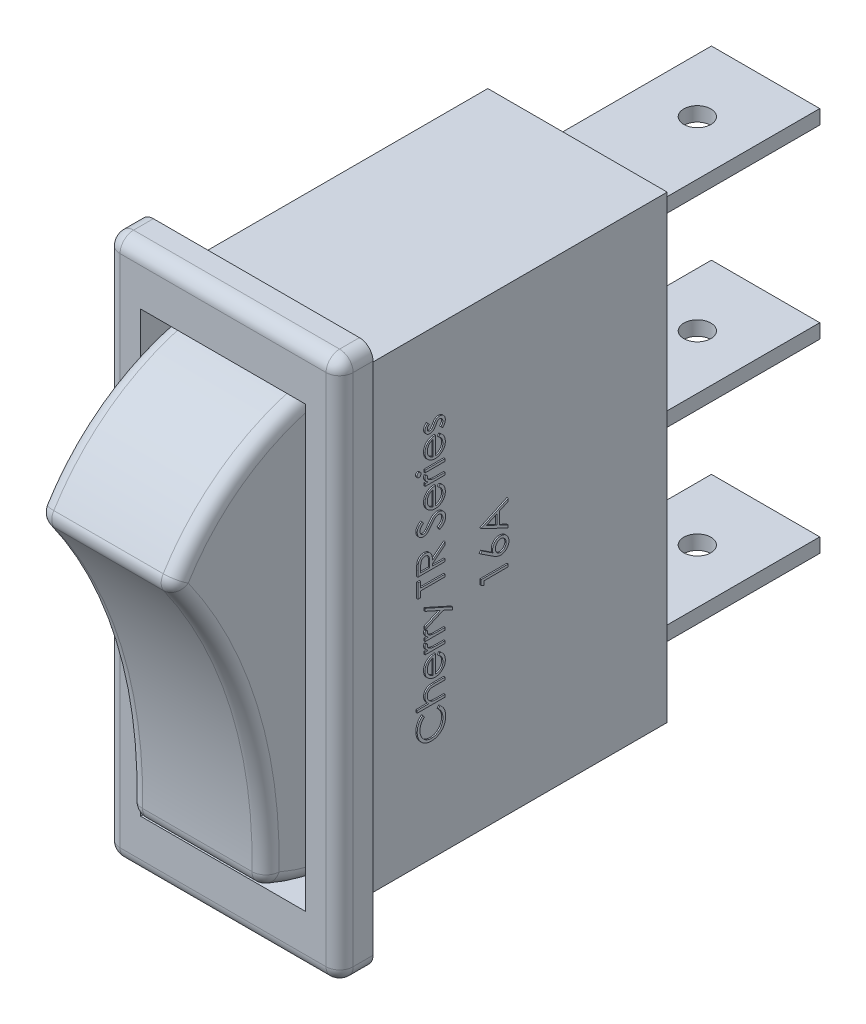
SolidWorks part; units mm, degrees
material "ABS"
ref_plane "Front Plane" through (0, 0, 0) normal (0, 0, 1) x (1, 0, 0)
ref_plane "Top Plane" through (0, 0, 0) normal (0, 1, 0) x (1, 0, 0)
ref_plane "Right Plane" through (0, 0, 0) normal (1, 0, 0) x (0, 0, -1)
sketch "Sketch1" plane through (0, 0, 0) normal (0, 0, 1) x (1, 0, 0)
  line L0 (0, -55) -> (0, 55) construction
  line L1 (-5.2578, 13.462) -> (5.2578, 13.462)
  line L2 (-5.2578, 13.462) -> (-5.2578, -13.462)
  line L3 (-5.2578, -13.462) -> (5.2578, -13.462)
  line L4 (5.2578, 13.462) -> (5.2578, -13.462)
  line L5 (55, 0) -> (-55, 0) construction
  point P4 (0, 13.462)
  point P7 (-5.2578, 0)
  dimension "D1" = 10.5156
  dimension "D2" = 26.924
extrude "main body" add sketch "Sketch1" against normal blind 18.8214
sketch "Sketch2" plane through (0, 0, 0) normal (0, 0, 1) x (1, 0, 0)
  line L4 (-5.2578, 13.462) -> (-5.2578, -13.462)
  line L5 (-5.2578, -13.462) -> (5.2578, -13.462)
  line L6 (5.2578, -13.462) -> (5.2578, 13.462)
  line L7 (5.2578, 13.462) -> (-5.2578, 13.462)
  line L8 (-5.2578, 13.462) -> (-5.2578, -13.462) construction
  line L9 (-5.2578, -13.462) -> (5.2578, -13.462) construction
  line L10 (5.2578, -13.462) -> (5.2578, 13.462) construction
  line L11 (5.2578, 13.462) -> (-5.2578, 13.462) construction
  line L16 (-4.464, 12.6683) -> (-4.464, -12.6682)
  line L17 (-4.464, -12.6682) -> (4.4641, -12.6682)
  line L18 (4.4641, -12.6682) -> (4.4641, 12.6682)
  line L19 (4.4641, 12.6682) -> (-4.464, 12.6683)
  line L20 (-4.464, 12.6683) -> (-4.464, -12.6682)
  line L21 (-4.464, -12.6682) -> (4.4641, -12.6682)
  line L22 (4.4641, -12.6682) -> (4.4641, 12.6682)
  line L23 (4.4641, 12.6682) -> (-4.464, 12.6683)
  dimension "D1" = 0
  dimension "D2" = 0.7937
extrude "main body light" cut sketch "Sketch2" against normal blind 17.4625
sketch "Sketch3" plane through (0, 0, 0) normal (0, 0, 1) x (1, 0, 0)
  line L0 (0, -10.3518) -> (0, 10.3518) construction
  line L1 (-6.8326, 15.875) -> (6.8326, 15.875)
  line L2 (-6.8326, 15.875) -> (-6.8326, -15.875)
  line L3 (-6.8326, -15.875) -> (6.8326, -15.875)
  line L4 (6.8326, 15.875) -> (6.8326, -15.875)
  line L5 (5.7836, 0) -> (-5.7836, 0) construction
  line L6 (-4.8326, 12.875) -> (4.8326, 12.875)
  line L7 (4.8326, 12.875) -> (4.8326, -12.875)
  line L8 (-4.8326, -12.875) -> (4.8326, -12.875)
  line L9 (-4.8326, 12.875) -> (-4.8326, -12.875)
  point P4 (0, 15.875)
  point P7 (-6.8326, 0)
  point P14 (-4.8326, 0)
  point P15 (0, 12.875)
  dimension "D1" = 13.6652
  dimension "D2" = 31.75
  dimension "D3" = 3
  dimension "D4" = 2
extrude "flange" add sketch "Sketch3" along normal blind 1.9558
sketch "Sketch4" plane through (0, 0, 0) normal (1, 0, 0) x (0, 0, -1)
  line L0 (8.8221, -10.3824) -> (3.9016, 0)
  line L1 (1.0592, 12.624) -> (3.9016, 0)
  line L2 (-1.9558, -15.875) -> (0, -15.875) construction
  line L3 (7.5159, 0) -> (-7.5159, 0) construction
  line L4 (-8.9408, 6.35) -> (-8.9408, -1.9309) construction
  line L5 (2.159, 0) -> (4.3189, 0) construction
  line L7 (-1.9558, -15.875) -> (-1.9558, 15.875) construction
  line L8 (-1.9558, 15.875) -> (0, 15.875) construction
  line L10 (1.0592, 15.4459) -> (1.0592, -1.9309) construction
  line L11 (1.0592, 6.35) -> (1.0592, -1.9309) construction
  line L12 (17.4625, 12.6682) -> (0, 12.6682) construction
  line L13 (-4.7056, -2.0778) -> (2.1432, 0.1504) construction
  arc A0 (-8.9408, 6.35) -> (-3.4798, -11.43) centre (-31.7201, -10.3752) cw
  arc A1 (-8.9408, 6.35) -> (0, 12.6682) centre (2.1432, 0.1504) cw
  circle A3 centre (2.159, 0) radius 1.5875
  arc A4 (0, 12.6682) -> (1.0592, 12.624) centre (0, -0.0318) cw
  arc A5 (6.9178, -11.8048) -> (8.8221, -10.3824) centre (0.3031, -0.9634) ccw
  arc A6 (-3.4798, -11.43) -> (6.9178, -11.8048) centre (2.1432, 0.1504) ccw
  point P12 (-0.9779, 15.875)
  dimension "D1" = 28.26
  dimension "D6" = 12.7
  dimension "D7" = 4.1148
  dimension "D8" = 3.175
  dimension "D2" = 6.985
  dimension "D3" = 9.525
  dimension "D4" = 1.524
  dimension "D5" = 4.445
  dimension "D9" = 10
  dimension "D10" = 167.332
  dimension "D11" = 12.9401
extrude "switch body and profile" add sketch "Sketch4" along normal mid plane 8 separate body
fillet "Fillet1" radius 0.7937 8 edges at (-6.8326, -15.875, 0.9779) (6.8326, -15.875, 0.9779) (-6.8326, 15.875, 0.9779) (6.8326, 15.875, 0.9779) (-6.8326, 0, 1.9558) (0, -15.875, 1.9558) (6.8326, 0, 1.9558) (0, 15.875, 1.9558)
fillet "Fillet2" radius 0.7937 8 edges at (0, 6.35, 8.9408) (-4, -12.7146, -1.6795) (4, -12.7146, -1.6795) (0, -11.43, 3.4798) (-4, -2.0778, 4.7056) (4, -2.0778, 4.7056) (4, 10.522, 5.1862) (-4, 10.522, 5.1862)
sketch "Sketch5" plane through (0, 0, -18.8214) normal (0, 0, -1) x (-1, 0, 0)
  line L0 (5.2578, -13.462) -> (-5.2578, -13.462) construction
  line L1 (-3.175, -10.5918) -> (3.175, -10.5918)
  line L2 (-3.175, -10.5918) -> (-3.175, -11.43)
  line L3 (-3.175, -11.43) -> (3.175, -11.43)
  line L4 (3.175, -10.5918) -> (3.175, -11.43)
  line L5 (0, 15.1853) -> (0, -15.1853) construction
  line L6 (-3.175, -0.5588) -> (3.175, -0.5588)
  line L7 (-3.175, 0.2794) -> (-3.175, -0.5588)
  line L8 (-3.175, 0.2794) -> (3.175, 0.2794)
  line L9 (3.175, 0.2794) -> (3.175, -0.5588)
  line L10 (-3.175, 10.3124) -> (3.175, 10.3124)
  line L11 (-3.175, 11.1506) -> (-3.175, 10.3124)
  line L12 (-3.175, 11.1506) -> (3.175, 11.1506)
  line L13 (3.175, 11.1506) -> (3.175, 10.3124)
  point P6 (0, -10.5918)
  dimension "D1" = 6.35
  dimension "D2" = 0.8382
  dimension "D3" = 2.032
  dimension "D4" = 10.033
extrude "Extrude5" add sketch "Sketch5" along normal blind 11.0236
hole_wizard "1/16 (0.0625) Diameter Hole1" positions "Sketch7" profile "Sketch6" hole size "1/16" standard "Ansi Inch" end condition through all
sketch "Sketch7" plane through (0, 11.1506, 0) normal (0, 1, 0) x (-1, 0, 0)
  line L0 (3.175, -29.845) -> (-3.175, -29.845) construction
  line L1 (0, 17.4625) -> (0, -17.4625) construction
  point P0 (0, -25.845)
  dimension "D1" = 4
sketch "Sketch6" plane through (0, 11.1506, -25.845) normal (1, 0, 0) x (0, 0, 1)
  line L0 (0, 0) -> (0, 27.0256)
  line L1 (0, 27.0256) -> (0.7937, 27.0256)
  line L2 (0.7937, 27.0256) -> (0.7937, 0)
  line L5 (0.7937, 0) -> (0, 0)
  line L11 (0, -6.35) -> (0, 107.95) construction
  dimension "Thru Hole Dia." = 1.5875
  dimension "Thru Hole Depth" = 27.0256
sketch "Sketch8" plane through (5.2578, 0, 0) normal (1, 0, 0) x (0, 0, -1)
  line L0 (5.7184, -8.3553) -> (5.7184, 9.6822) construction
  text T0 "Cherry TR Series\r\n16A" font "Century Gothic" height 1.5875
extrude "label text" add sketch "Sketch8" along normal blind 0.0762
sketch "cut pattern" plane through (0, 0, 0) normal (0, 0, -1) x (-1, 0, 0)
  line L0 (5.4991, 15.367) -> (-5.4991, 15.367)
  line L1 (-5.4991, 15.367) -> (-5.4991, -15.367)
  line L2 (-5.4991, -15.367) -> (5.4991, -15.367)
  line L3 (5.4991, -15.367) -> (5.4991, 15.367)
  line L4 (5.2578, -13.462) -> (5.2578, 13.462)
  line L5 (-5.2578, -13.462) -> (5.2578, -13.462)
  line L6 (-5.2578, 13.462) -> (-5.2578, -13.462)
  line L7 (5.2578, 13.462) -> (-5.2578, 13.462)
  line L8 (5.2578, -13.462) -> (5.2578, 13.462) construction
  line L9 (-5.2578, -13.462) -> (5.2578, -13.462) construction
  line L10 (-5.2578, 13.462) -> (-5.2578, -13.462) construction
  line L11 (5.2578, 13.462) -> (-5.2578, 13.462) construction
  line L13 (0, 0) -> (0, 16.6508) construction
  line L14 (0, 0) -> (-10.6607, 0) construction
  dimension "D2" = 10.9982
  dimension "D3" = 30.734
  dimension "D1" = 0
